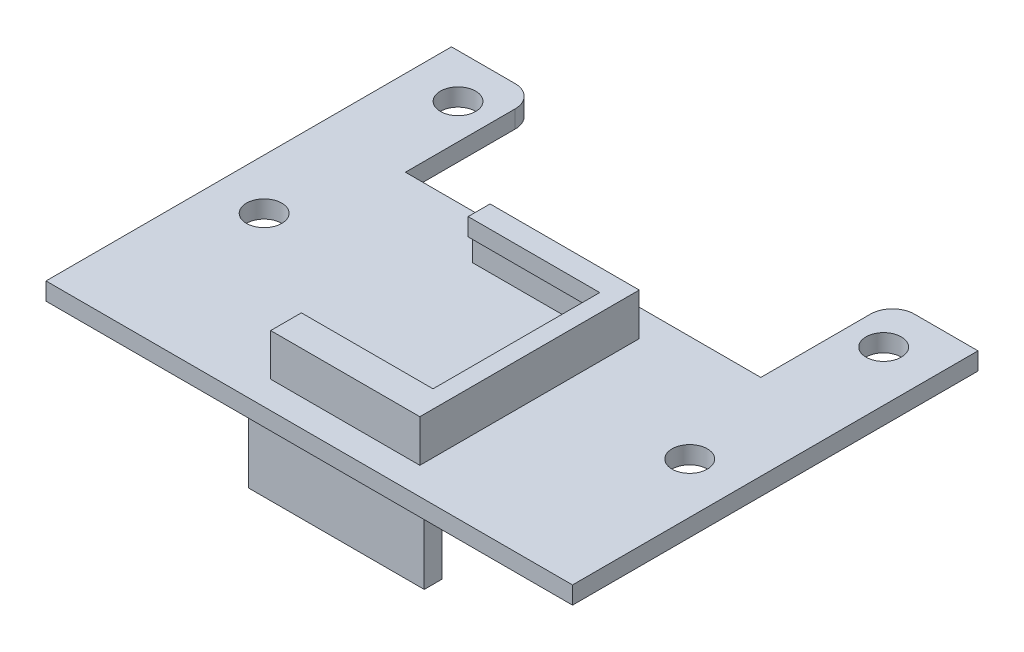
SolidWorks part; units mm, degrees
ref_plane "Front Plane" through (0, 0, 0) normal (0, 0, 1) x (1, 0, 0)
ref_plane "Top Plane" through (0, 0, 0) normal (0, 1, 0) x (1, 0, 0)
ref_plane "Right Plane" through (0, 0, 0) normal (1, 0, 0) x (0, 0, -1)
sketch "Sketch1" plane through (0, 0, 0) normal (0, 1, 0) x (1, 0, 0)
  line L0 (0, 0) -> (0, 10.0958) construction
  line L1 (38.1, -20.3835) -> (-38.1, -20.3835)
  line L2 (38.1, -20.3835) -> (38.1, 20.3835)
  line L3 (38.1, 20.3835) -> (-38.1, 20.3835) construction
  line L4 (-38.1, -20.3835) -> (-38.1, 20.3835)
  line L5 (38.1, -20.3835) -> (-38.1, 20.3835) construction
  line L6 (38.1, 20.3835) -> (-38.1, -20.3835) construction
  line L7 (0, 0) -> (9.14, 0) construction
  line L13 (-25.7175, 17.2085) -> (-25.7175, 1.3335)
  line L14 (-38.1, 20.3835) -> (-28.8925, 20.3835)
  line L15 (-25.7175, 1.3335) -> (25.7175, 1.3335)
  line L16 (25.7175, 17.2085) -> (25.7175, 1.3335)
  line L17 (38.1, 20.3835) -> (28.8925, 20.3835)
  circle A0 centre (30.7975, -14.0335) radius 2.5527
  circle A2 centre (30.7975, 14.0335) radius 2.5527
  circle A3 centre (-30.7975, -14.0335) radius 2.5527
  circle A4 centre (-30.7975, 14.0335) radius 2.5527
  arc A7 (-25.7175, 17.2085) -> (-28.8925, 20.3835) centre (-28.8925, 17.2085) ccw
  arc A8 (25.7175, 17.2085) -> (28.8925, 20.3835) centre (28.8925, 17.2085) cw
  point P0 (0, 0)
  point P19 (0, 1.3335)
  point P22 (0, 14.0335)
  point P23 (-25.7175, 20.3835)
  point P24 (12.7, 14.0335)
  point P27 (-12.7, 14.0335)
  point P30 (25.7175, 20.3835)
  dimension "D3" = 5.1054
  dimension "D6" = 28.067
  dimension "D7" = 5.1054
  dimension "D10" = 5.08
  dimension "D12" = 3.175
  dimension "D1" = 6.35
  dimension "D2" = 76.2
  dimension "D4" = 6.35
  dimension "D5" = 7.3025
  dimension "D8" = 7.3025
  dimension "D9" = 12.7
  dimension "D11" = 19.05
extrude "Boss-Extrude1" add sketch "Sketch1" along normal blind 2.54
sketch "Sketch7" plane through (0, 2.54, 0) normal (0, 1, 0) x (1, 0, 0)
  line L1 (-38.1, -20.3835) -> (38.1, -20.3835)
  line L2 (-38.1, -20.3835) -> (-38.1, -38.2989)
  line L3 (-38.1, -38.2989) -> (38.1, -38.2989)
  line L4 (38.1, -20.3835) -> (38.1, -38.2989)
  dimension "D1" = 17.9154
extrude "Boss-Extrude5" add sketch "Sketch7" against normal up to surface (2.54 mm away) up to face at (0, 0, -7.9166)
sketch "Sketch3" plane through (0, 2.54, 0) normal (0, 1, 0) x (1, 0, 0)
  line L0 (0, 1.3335) -> (0, -38.2989) construction
  line L1 (-12.065, -2.6077) -> (-12.065, -5.1477)
  line L2 (9.525, -31.8177) -> (-9.525, -31.8177)
  line L3 (9.525, -31.8177) -> (9.525, -5.1477)
  line L4 (9.525, -5.1477) -> (-9.525, -5.1477)
  line L5 (-9.525, -31.8177) -> (-9.525, -5.1477) construction
  line L6 (9.525, -31.8177) -> (-9.525, -5.1477) construction
  line L7 (9.525, -5.1477) -> (-9.525, -31.8177) construction
  line L8 (12.065, -34.3577) -> (-12.065, -34.3577)
  line L9 (12.065, -34.3577) -> (12.065, -2.6077)
  line L10 (12.065, -2.6077) -> (-12.065, -2.6077)
  line L11 (-12.065, -34.3577) -> (-12.065, -2.6077) construction
  line L12 (12.065, -34.3577) -> (-12.065, -2.6077) construction
  line L13 (12.065, -2.6077) -> (-12.065, -34.3577) construction
  line L14 (-12.065, -5.1477) -> (-9.525, -5.1477)
  line L15 (-12.065, -31.8177) -> (-9.525, -31.8177)
  line L20 (-12.065, -31.8177) -> (-12.065, -34.3577)
  line L21 (25.7175, 1.3335) -> (-25.7175, 1.3335) construction
  line L22 (-38.1, -38.2989) -> (38.1, -38.2989) construction
  point P2 (0, -18.4827)
  point P7 (0, -18.4827)
  point P21 (0, -18.4827)
  dimension "D1" = 26.67
  dimension "D2" = 19.05
extrude "Boss-Extrude2" add sketch "Sketch3" along normal blind 3.556 contours L20 L8 L9 L10 L1 L14 L4 L3 L2 L15
sketch "Sketch4" plane through (-12.065, 0, 0) normal (-1, 0, 0) x (0, 0, 1)
  line L1 (2.6077, 6.096) -> (34.3577, 6.096)
  line L2 (2.6077, 6.096) -> (2.6077, 2.54)
  line L3 (2.6077, 2.54) -> (34.3577, 2.54)
  line L4 (34.3577, 6.096) -> (34.3577, 2.54)
extrude "Cut-Extrude1" cut sketch "Sketch4" against normal blind 2.54
sketch "Sketch5" plane through (0, 6.096, 0) normal (0, 1, 0) x (1, 0, 0)
  line L0 (-9.525, -2.6077) -> (-9.525, -5.7827)
  line L1 (-9.525, -2.6077) -> (-9.525, -5.7827) construction
  line L2 (12.065, -2.6077) -> (-9.525, -2.6077)
  line L3 (12.065, -2.6077) -> (12.065, -34.3577)
  line L4 (12.065, -34.3577) -> (-9.525, -34.3577)
  line L5 (-9.525, -2.6077) -> (-9.525, -34.3577) construction
  line L6 (9.525, -5.7827) -> (-9.525, -5.7827)
  line L7 (9.525, -5.7827) -> (9.525, -29.9127)
  line L8 (9.525, -29.9127) -> (-9.525, -29.9127)
  line L9 (-9.525, -5.7827) -> (-9.525, -29.9127) construction
  line L10 (-9.525, -29.9127) -> (-9.525, -34.3577)
  line L11 (12.065, -34.3577) -> (12.065, -2.6077) construction
  line L12 (12.065, -34.3577) -> (-9.525, -34.3577) construction
  dimension "D1" = 3.175
  dimension "D2" = 2.54
  dimension "D3" = 4.445
  dimension "D4" = 0
  dimension "D5" = 0
extrude "Boss-Extrude3" add sketch "Sketch5" along normal blind 2.54
sketch "Sketch6" plane through (0, 0, 0) normal (0, -1, 0) x (-1, 0, 0)
  line L0 (0, 1.3335) -> (0, -38.2989) construction
  line L1 (-25.7175, 1.3335) -> (25.7175, 1.3335) construction
  line L3 (38.1, -38.2989) -> (-38.1, -38.2989) construction
  line L5 (22.86, -18.4827) -> (22.86, -23.5627)
  line L6 (22.86, -5.1477) -> (-22.86, -5.1477) construction
  line L7 (22.86, -5.1477) -> (22.86, -31.8177) construction
  line L8 (22.86, -31.8177) -> (-22.86, -31.8177) construction
  line L9 (-22.86, -5.1477) -> (-22.86, -31.8177) construction
  line L10 (22.86, -5.1477) -> (-22.86, -31.8177) construction
  line L11 (22.86, -31.8177) -> (-22.86, -5.1477) construction
  line L12 (22.86, -23.5627) -> (25.4, -23.5627)
  line L13 (25.4, -23.5627) -> (25.4, -13.4027)
  line L14 (25.4, -13.4027) -> (22.86, -13.4027)
  line L15 (22.86, -13.4027) -> (22.86, -23.5627)
  line L16 (0, -31.8177) -> (12.7, -31.8177)
  line L17 (12.7, -31.8177) -> (12.7, -34.3577)
  line L18 (12.7, -34.3577) -> (-12.7, -34.3577)
  line L19 (-12.7, -34.3577) -> (-12.7, -31.8177)
  line L20 (-12.7, -31.8177) -> (0, -31.8177)
  line L21 (-12.7, -2.6077) -> (-12.7, -5.1477)
  line L22 (12.7, -2.6077) -> (-12.7, -2.6077)
  line L23 (12.7, -5.1477) -> (12.7, -2.6077)
  line L24 (0, -5.1477) -> (12.7, -5.1477)
  line L25 (-12.7, -5.1477) -> (0, -5.1477)
  point P6 (-6.35, -31.8177)
  point P7 (0, -18.4827)
  point P8 (0, -18.4827)
  dimension "D1" = 26.67
  dimension "D2" = 45.72
  dimension "D3" = 5.08
  dimension "D4" = 10.16
  dimension "D5" = 2.54
  dimension "D6" = 12.7
  dimension "D7" = 25.4
  dimension "D8" = 2.54
  dimension "D9" = 26.67
  dimension "D10" = 2.54
extrude "Boss-Extrude4" add sketch "Sketch6" along normal blind 12.7 contours L14 L15 L5 L12 L13 | L21 L25 L24 L23 L22 | L20 L16 L17 L18 L19
